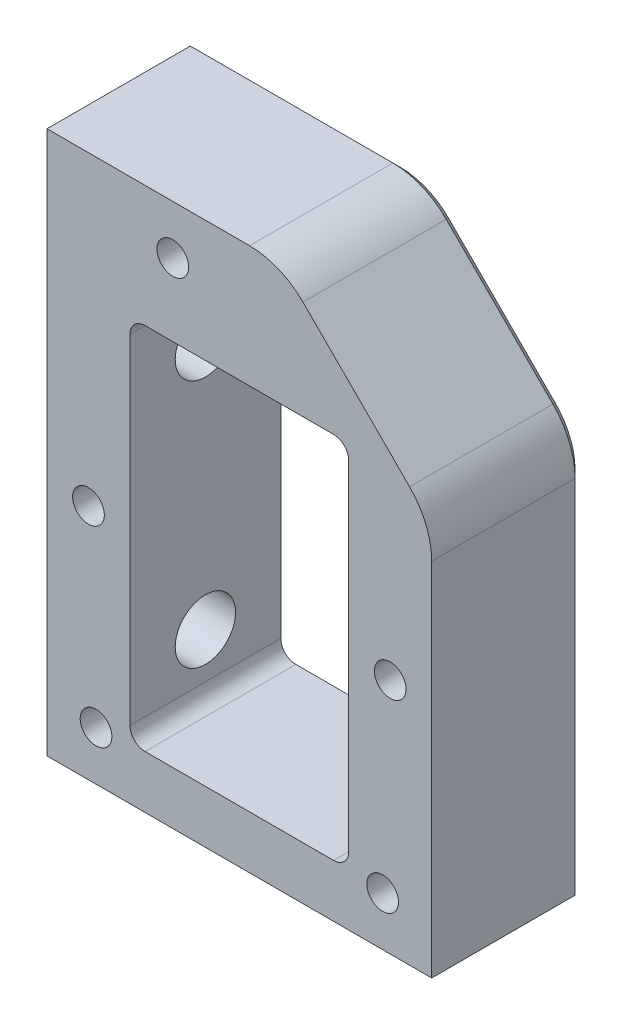
SolidWorks part; units mm, degrees
material "ABS"
ref_plane "Front Plane" through (0, 0, 0) normal (0, 0, 1) x (1, 0, 0)
ref_plane "Top Plane" through (0, 0, 0) normal (0, 1, 0) x (1, 0, 0)
ref_plane "Right Plane" through (0, 0, 0) normal (1, 0, 0) x (0, 0, -1)
sketch "Sketch1" plane through (0, 0, 0) normal (0, 0, 1) x (1, 0, 0)
  line L0 (-11.5, -23.45) -> (11.5, -23.45) construction
  line L1 (14.5, 24.45) -> (-14.5, 24.45)
  line L2 (14.5, 24.45) -> (14.5, -24.45)
  line L3 (14.5, -24.45) -> (-14.5, -24.45)
  line L4 (-14.5, 24.45) -> (-14.5, -24.45)
  line L5 (13.5, -21.45) -> (13.5, 17.45) construction
  line L6 (-13.5, 17.45) -> (-13.5, -21.45) construction
  line L7 (7.5, 23.45) -> (-7.5, 23.45) construction
  line L8 (-25.5, -31.45) -> (-25.5, 428.55) construction
  line L9 (-25.5, 40.55) -> (5.5, 40.55)
  line L10 (-25.5, 40.55) -> (-25.5, -31.45)
  line L11 (-25.5, -31.45) -> (25.5, -31.45)
  line L12 (25.5, 20.55) -> (25.5, -31.45)
  line L13 (-45.5, -31.45) -> (254.5, -31.45) construction
  line L16 (25.5, 20.55) -> (5.5, 40.55)
  dimension "D5" = 51
  dimension "D1" = 1
  dimension "D2" = 1
  dimension "D3" = 1
  dimension "D4" = 1
  dimension "D6" = 45
  dimension "D7" = 31
  dimension "D8" = 72
extrude "Boss-Extrude1" add sketch "Sketch1" along normal blind 20
sketch "Sketch2" plane through (0, 0, 0) normal (0, 0, -1) x (-1, 0, 0)
  circle A0 centre (-20, 0) radius 2.1
  circle A1 centre (20, 0) radius 2.1
  dimension "D1" = 4.2
extrude "Cut-Extrude1" cut sketch "Sketch2" against normal through all
fillet "Fillet1" radius 2 4 edges at (-14.5, -24.45, 10) (14.5, -24.45, 10) (14.5, 24.45, 10) (-14.5, 24.45, 10)
fillet "Fillet2" radius 10 2 edges at (25.5, 20.55, 10) (5.5, 40.55, 10)
chamfer "Chamfer1" distance 1 angle 45 5 edges at (25.5, -7.5211, 0) (-12.0711, 40.55, 0) (24.7388, 20.2347, 0) (5.1847, 39.7888, 0) (15.5, 30.55, 0)
sketch "Sketch3" plane through (-25.5, 0, 0) normal (-1, 0, 0) x (0, 0, 1)
  line L0 (10, -31.45) -> (10, 40.55) construction
  line L1 (20, -31.45) -> (0, -31.45) construction
  line L2 (20, 40.55) -> (1, 40.55) construction
  circle A0 centre (10, 16.55) radius 2.1
  circle A1 centre (10, -16.45) radius 2.1
  dimension "D1" = 4.2
  dimension "D2" = 24
  dimension "D3" = 15
extrude "Cut-Extrude2" cut sketch "Sketch3" against normal up to next
ref_plane "Plane1" through (-20.5, 0, 0) normal (-1, 0, 0) x (0, 0, 1)
sketch "Sketch4" plane through (-20.5, 0, 0) normal (-1, 0, 0) x (0, 0, 1)
  circle A0 centre (10, 16.55) radius 4
  circle A1 centre (10, -16.45) radius 4
  dimension "D1" = 8
extrude "Cut-Extrude3" cut sketch "Sketch4" against normal up to next
sketch "Sketch5" plane through (0, 0, 20) normal (0, 0, 1) x (1, 0, 0)
  line L10 (19, -24.95) -> (19, 16.4079)
  line L11 (17.9749, 18.8827) -> (3.8327, 33.0249)
  line L12 (1.3579, 34.05) -> (-19, 34.05)
  line L13 (-19, 34.05) -> (-19, -24.95)
  line L14 (-19, -24.95) -> (19, -24.95)
  line L15 (19, -24.95) -> (19, 16.4079) construction
  line L16 (17.9749, 18.8827) -> (3.8327, 33.0249) construction
  line L17 (1.3579, 34.05) -> (-19, 34.05) construction
  line L18 (-19, 34.05) -> (-19, -24.95) construction
  line L19 (-19, -24.95) -> (19, -24.95) construction
  circle A2 centre (19, -24.95) radius 2.1
  circle A3 centre (-8.8211, 34.05) radius 2.1
  arc A4 (19, 16.4079) -> (17.9749, 18.8827) centre (15.5, 16.4079) ccw
  arc A5 (3.8327, 33.0249) -> (1.3579, 34.05) centre (1.3579, 30.55) ccw
  arc A6 (19, 16.4079) -> (17.9749, 18.8827) centre (15.5, 16.4079) ccw construction
  arc A7 (3.8327, 33.0249) -> (1.3579, 34.05) centre (1.3579, 30.55) ccw construction
  circle A8 centre (-19, -24.95) radius 2.1
  dimension "D2" = 4.2
  dimension "D1" = 6.5
extrude "Cut-Extrude4" cut sketch "Sketch5" against normal blind 10
